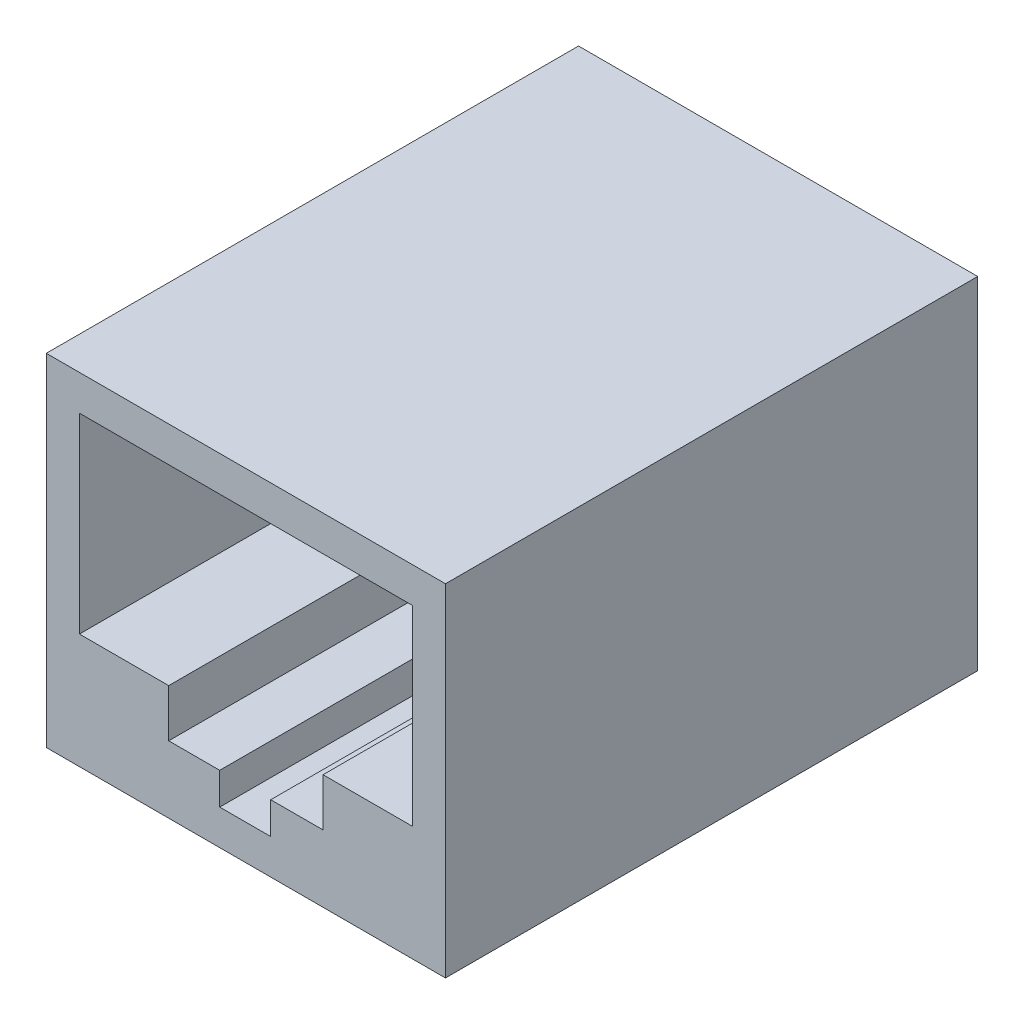
SolidWorks part; units mm, degrees
ref_plane "Front Plane" through (0, 0, 0) normal (0, 0, 1) x (1, 0, 0)
ref_plane "Top Plane" through (0, 0, 0) normal (0, 1, 0) x (1, 0, 0)
ref_plane "Right Plane" through (0, 0, 0) normal (1, 0, 0) x (0, 0, -1)
sketch "Sketch1" plane through (0, 0, 0) normal (0, 0, 1) x (1, 0, 0)
  line L1 (0, 0) -> (15.9, 0)
  line L2 (0, 0) -> (0, 13.6)
  line L3 (0, 13.6) -> (15.9, 13.6)
  line L4 (15.9, 0) -> (15.9, 13.6)
  dimension "D1" = 13.6
  dimension "D2" = 15.9
extrude "Boss-Extrude1" add sketch "Sketch1" against normal blind 21.2
sketch "Sketch2" plane through (0, 0, 0) normal (0, 0, 1) x (1, 0, 0)
  line L0 (0, 13.6) -> (0, 0) construction
  line L1 (1.32, 12.1944) -> (14.58, 12.1944)
  line L2 (1.32, 12.1944) -> (1.32, 4.5744)
  line L3 (1.32, 4.5744) -> (4.876, 4.5744)
  line L4 (14.58, 12.1944) -> (14.58, 4.5744)
  line L5 (15.9, 0) -> (15.9, 13.6) construction
  line L6 (11.024, 4.5744) -> (14.58, 4.5744)
  line L7 (4.876, 2.6694) -> (6.908, 2.6694)
  line L8 (4.876, 4.5744) -> (4.876, 2.6694)
  line L9 (8.94, 2.6694) -> (11.024, 2.6694)
  line L10 (11.024, 4.5744) -> (11.024, 2.6694)
  line L12 (6.908, 2.6694) -> (6.908, 1.3994)
  line L13 (6.908, 1.3994) -> (8.94, 1.3994)
  line L14 (8.94, 2.6694) -> (8.94, 1.3994)
  dimension "D1" = 13.26
  dimension "D2" = 1.32
  dimension "D3" = 1.32
  dimension "D4" = 7.62
  dimension "D5" = 3.556
  dimension "D6" = 3.556
  dimension "D7" = 1.905
  dimension "D8" = 1.905
  dimension "D9" = 1.27
  dimension "D10" = 2.032
  dimension "D11" = 2.032
extrude "Cut-Extrude1" cut sketch "Sketch2" against normal blind 15.24
